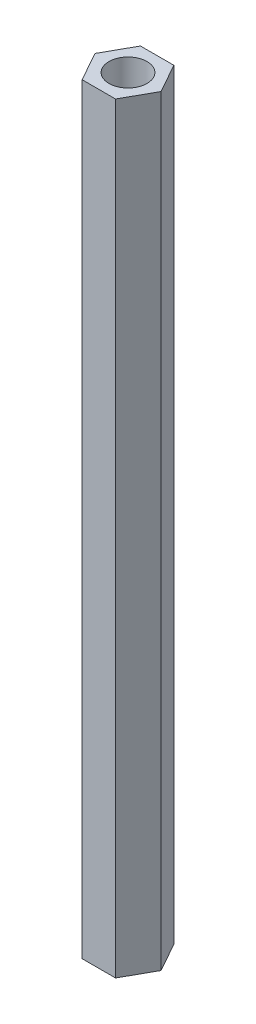
SolidWorks part; units mm, degrees
ref_plane "前视基准面" through (0, 0, 0) normal (0, 0, 1) x (1, 0, 0)
ref_plane "上视基准面" through (0, 0, 0) normal (0, 1, 0) x (1, 0, 0)
ref_plane "右视基准面" through (0, 0, 0) normal (1, 0, 0) x (0, 0, -1)
other "Configuration Table"
sketch "草图1" plane through (0, 0, 0) normal (0, 1, 0) x (1, 0, 0)
  line L1 (1.3169, -2.3) -> (2.6, 0)
  line L2 (2.6, 0) -> (1.3169, 2.3)
  line L3 (1.3169, 2.3) -> (-1.3169, 2.3)
  line L4 (-1.3169, 2.3) -> (-2.6, 0)
  line L5 (-2.6, 0) -> (-1.3169, -2.3)
  line L6 (-1.3169, -2.3) -> (1.3169, -2.3)
  circle A0 centre (0, 0) radius 1.5
  point P1 (0, 2.3)
  point P9 (0, -2.3)
  dimension "D3" = 3
  dimension "D1" = 4.6
  dimension "D2" = 5.2
extrude "凸台-拉伸1" add sketch "草图1" along normal blind 60
